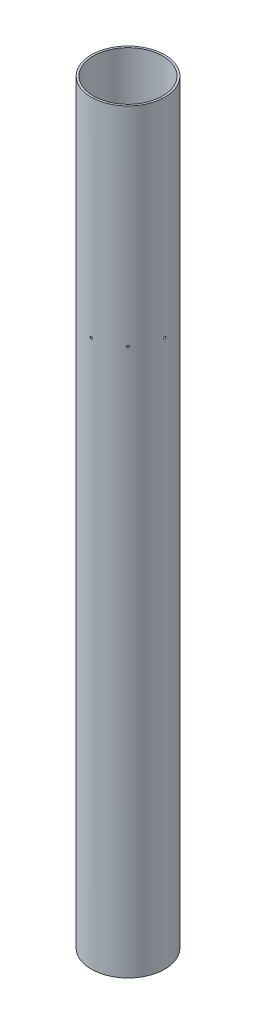
SolidWorks part; units mm, degrees
material "Hexcel AS4C (3000 Filaments)"
ref_plane "Front Plane" through (0, 0, 0) normal (0, 0, 1) x (1, 0, 0)
ref_plane "Top Plane" through (0, 0, 0) normal (0, 1, 0) x (1, 0, 0)
ref_plane "Right Plane" through (0, 0, 0) normal (1, 0, 0) x (0, 0, -1)
sketch "Sketch1" plane through (0, 0, 0) normal (0, 1, 0) x (1, 0, 0)
  circle A0 centre (0, 0) radius 50.8
  dimension "D1" = 101.6
extrude "Body Tube Extrusion" add sketch "Sketch1" along normal blind 1104.9 thin
ref_plane "Plane1" through (0, 0, 53.721) normal (0, 0, 1) x (1, 0, 0)
sketch "Sketch2" plane through (0, 0, 53.721) normal (0, 0, 1) x (1, 0, 0)
  line L0 (0, 1104.9) -> (0, 0) construction
  line L1 (50.8, 1104.9) -> (-50.8, 1104.9) construction
  line L2 (-53.721, 0) -> (53.721, 0) construction
  circle A0 centre (0, 800.1) radius 1.6383
  dimension "D1" = 3.2766
  dimension "D2" = 800.1
extrude "Bulkhead Hole" cut sketch "Sketch2" against normal up to next
pattern_circular "CirPattern1" count 8 over 360 about axis through (0, 1104.9, 0) along (0, -1, 0) of "Bulkhead Hole"
